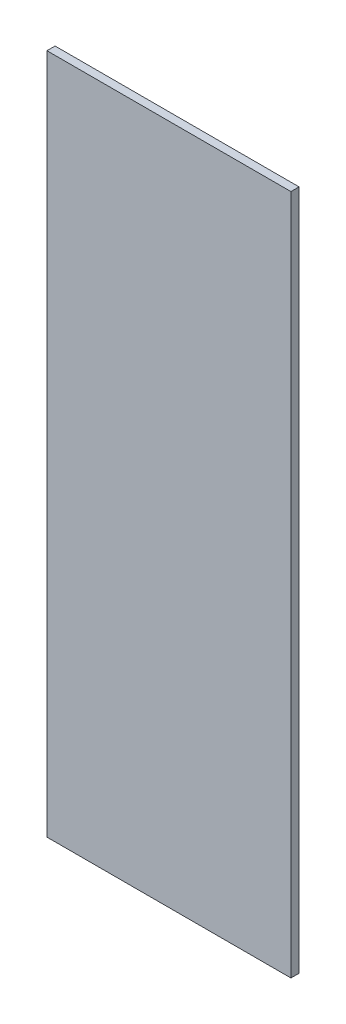
SolidWorks part; units mm, degrees
ref_plane "Спереди" through (0, 0, 0) normal (0, 0, 1) x (1, 0, 0)
ref_plane "Сверху" through (0, 0, 0) normal (0, 1, 0) x (1, 0, 0)
ref_plane "Справа" through (0, 0, 0) normal (1, 0, 0) x (0, 0, -1)
sketch "Эскиз1" plane through (0, 0, 0) normal (0, 1, 0) x (1, 0, 0)
  line L1 (0, 0) -> (150, 0)
  line L2 (0, 0) -> (0, -5)
  line L3 (0, -5) -> (150, -5)
  line L4 (150, 0) -> (150, -5)
extrude "Вытянуть1" add sketch "Эскиз1" along normal up to surface (418.7137 mm away)
sketch "Эскиз2" plane through (0, 0, 5) normal (0, 0, 1) x (1, 0, 0)
  line L0 (75, 50) -> (75, 80.7754) construction
